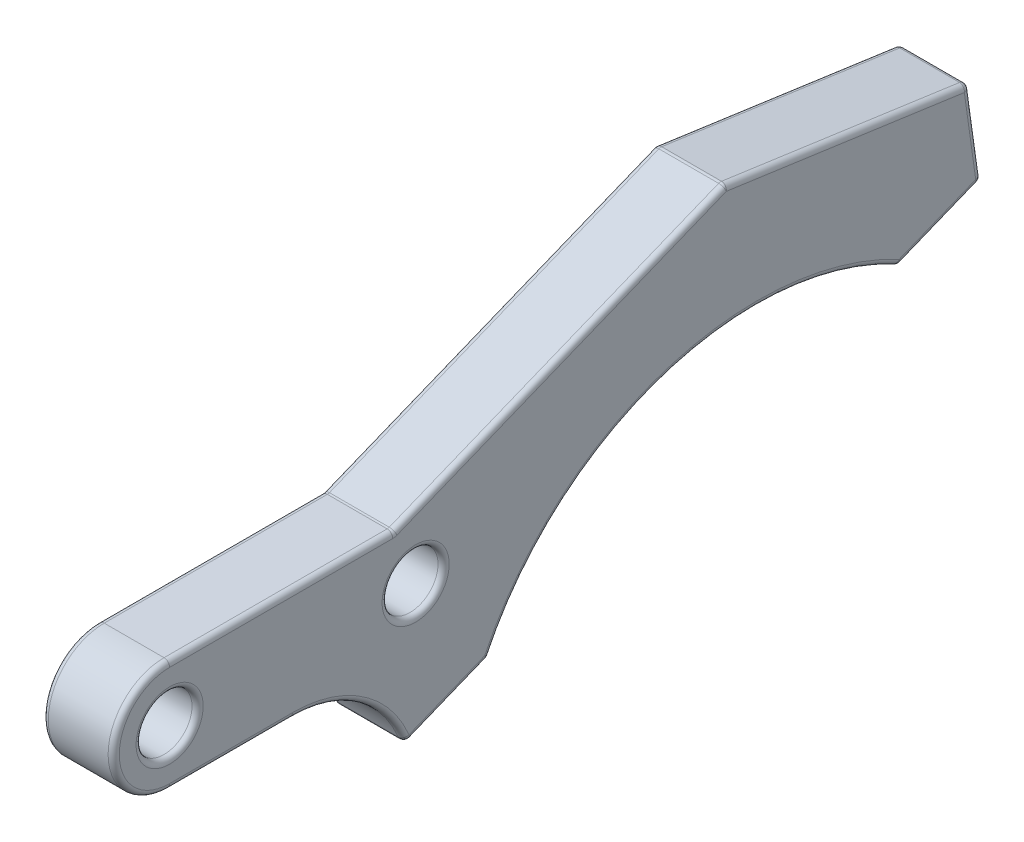
SolidWorks part; units mm, degrees
material "AISI 304"
ref_plane "Plano frontal" through (0, 0, 0) normal (0, 0, 1) x (1, 0, 0)
ref_plane "Plano superior" through (0, 0, 0) normal (0, 1, 0) x (1, 0, 0)
ref_plane "Plano direito" through (0, 0, 0) normal (1, 0, 0) x (0, 0, -1)
sketch "Esboço2" plane through (0, 0, 0) normal (1, 0, 0) x (0, 0, -1)
  line L0 (-26.5167, 0) -> (-4.5167, 0) construction
  line L1 (-26.5167, 5) -> (-6.4667, 5)
  line L2 (-26.5167, -5) -> (-15.5167, -5)
  line L3 (-6.4667, 5) -> (23.2033, 16.9875)
  line L4 (23.2033, 16.9875) -> (44.9933, 13.9251)
  line L5 (44.9933, 13.9251) -> (46.1176, 5.9251)
  line L6 (46.1176, 5.9251) -> (38.7002, 2.9282)
  line L7 (2.0244, -9.0749) -> (-5.3931, -12.0718)
  arc A0 (-26.5167, 5) -> (-26.5167, -5) centre (-26.5167, 0) ccw
  circle A2 centre (-26.5167, 0) radius 2.5
  circle A3 centre (-4.5167, 0) radius 2.5
  arc A4 (38.7002, 2.9282) -> (2.0244, -9.0749) centre (26.0543, -20.4654) ccw
  arc A5 (-5.3931, -12.0718) -> (-15.5167, -5) centre (-15.5167, -15.7821) ccw
  point P3 (-15.5167, 0)
  dimension "D2" = 5
  dimension "D3" = 22
  dimension "D14" = 38.59
  dimension "D15" = 5
  dimension "D1" = 10
  dimension "D4" = 158
  dimension "D5" = 20.05
  dimension "D6" = 29.67
  dimension "D7" = 30
  dimension "D8" = 254
  dimension "D9" = 21.79
  dimension "D10" = 8
  dimension "D11" = 8
  dimension "D12" = 8
  dimension "D13" = 7.03
extrude "Ressalto-extrusão1" add sketch "Esboço2" along normal mid plane 6.35
fillet "Filete1" radius 0.5 30 edges at (3.175, 0, 31.5167) (-3.175, 0, 31.5167) (3.175, 0, 24.0167) (3.175, 5, 16.4917) (-3.175, 5, 16.4917) (3.175, 15.4563, -34.0983) (-3.175, 15.4563, -34.0983) (0, 16.9875, -23.2033) (3.175, 10.9937, -8.3683) (0, 5, 6.4667) (-3.175, 10.9937, -8.3683) (3.175, 4.4266, -42.4089) (-3.175, 4.4266, -42.4089) (0, 5.9251, -46.1176) (3.175, 9.9251, -45.5555) (0, 13.9251, -44.9933) (-3.175, 9.9251, -45.5555) (3.175, -5, 21.0167) (-3.175, -5, 21.0167) (3.175, -6.943, 9.3422) (-3.175, -6.943, 9.3422) (0, -12.0718, 5.3931) (3.175, -10.5733, 1.6843) (-3.175, -10.5733, 1.6843) (0, -9.0749, -2.0244) (3.175, 4.8083, -17.7828) (0, 2.9282, -38.7002) (-3.175, 4.8083, -17.7828) (-3.175, 0, 2.0167) (3.175, 0, 2.0167)
